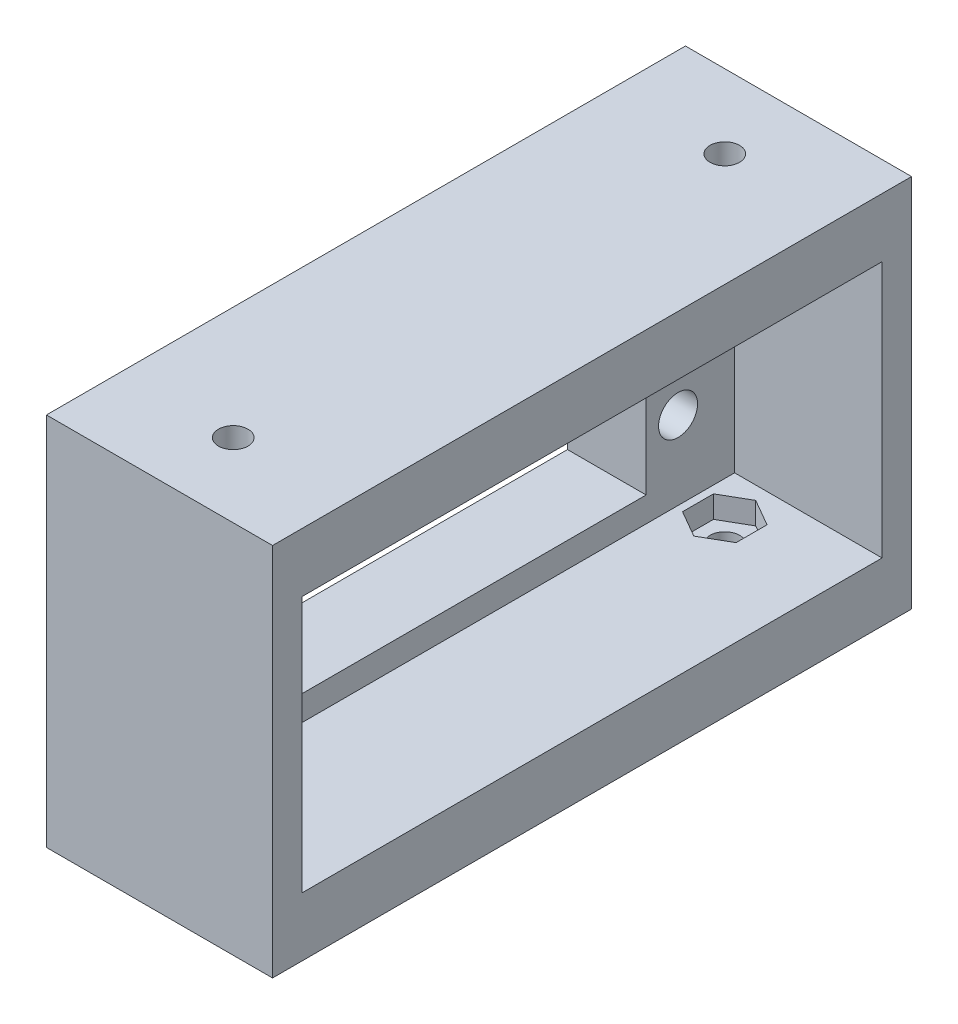
SolidWorks part; units mm, degrees
ref_plane "Front Plane" through (0, 0, 0) normal (0, 0, 1) x (1, 0, 0)
ref_plane "Top Plane" through (0, 0, 0) normal (0, 1, 0) x (1, 0, 0)
ref_plane "Right Plane" through (0, 0, 0) normal (1, 0, 0) x (0, 0, -1)
sketch "Sketch1" plane through (0, 0, 0) normal (1, 0, 0) x (0, 0, -1)
  line L0 (-20.5, 10.5) -> (20.5, 10.5)
  line L1 (-20.5, 10.5) -> (-20.5, -10.5)
  line L2 (-20.5, -10.5) -> (20.5, -10.5)
  line L3 (20.5, 10.5) -> (20.5, -10.5)
  line L5 (-32.5, 19.05) -> (32.5, 19.05)
  line L6 (-32.5, 19.05) -> (-32.5, -19.05)
  line L7 (-32.5, -19.05) -> (32.5, -19.05)
  line L8 (32.5, 19.05) -> (32.5, -19.05)
  point P4 (0, 10.5)
  point P6 (20.5, 0)
  point P11 (0, 19.05)
  point P12 (32.5, 0)
  dimension "D1" = 41
  dimension "D2" = 21
  dimension "D3" = 12
  dimension "D4" = 19.05
extrude "Boss-Extrude1" add sketch "Sketch1" along normal blind 8
sketch "Sketch2" plane through (8, 0, 0) normal (1, 0, 0) x (0, 0, -1)
  line L1 (-32.5, 19.05) -> (32.5, 19.05)
  line L2 (-32.5, 19.05) -> (-32.5, -19.05)
  line L3 (-32.5, -19.05) -> (32.5, -19.05)
  line L4 (32.5, 19.05) -> (32.5, -19.05)
  line L5 (-29.5, 13.05) -> (29.5, 13.05)
  line L6 (-29.5, 13.05) -> (-29.5, -13.05)
  line L7 (-29.5, -13.05) -> (29.5, -13.05)
  line L8 (29.5, 13.05) -> (29.5, -13.05)
  point P10 (0, -13.05)
  point P12 (-29.5, 0)
  dimension "D1" = 6
  dimension "D2" = 3
extrude "Boss-Extrude2" add sketch "Sketch2" along normal blind 15
hole_wizard "5/32 (0.15625) Diameter Hole1" positions "Sketch3" profile "Sketch4" hole size "5/32" standard "ANSI Inch" end condition through all
sketch "Sketch3" plane through (0, 0, 0) normal (-1, 0, 0) x (0, 0, 1)
  line L0 (23.749, 5.08) -> (23.749, -5.08) construction
  line L1 (23.749, -5.08) -> (-23.749, -5.08) construction
  line L2 (-23.749, -5.08) -> (-23.749, 5.08) construction
  line L3 (-23.749, 5.08) -> (23.749, 5.08) construction
  point P0 (-23.6085, 5.1229)
  point P2 (-23.749, -5.08)
  point P4 (23.749, -5.08)
  point P7 (23.749, 5.08)
sketch "Sketch4" plane through (0, 5.1229, -23.6085) normal (0, 1, 0) x (0, 0, 1)
  line L0 (0, 0) -> (0, 23)
  line L1 (0, 23) -> (1.9844, 23)
  line L2 (1.9844, 23) -> (1.9844, 0)
  line L5 (1.9844, 0) -> (0, 0)
  line L11 (0, -6.35) -> (0, 107.95) construction
  dimension "Thru Hole Dia." = 3.9688
  dimension "Thru Hole Depth" = 23
hole_wizard "Ø3.0mm Dowel Hole1" positions "Sketch5" profile "Sketch6" hole size "Ø3.0" standard "ANSI Metric"
sketch "Sketch5" plane through (0, -13.05, 0) normal (0, 1, 0) x (1, 0, 0)
  line L0 (11.5, 25) -> (11.5, -25) construction
  line L2 (0, 0) -> (23, 0) construction
  line L3 (0, 32.5) -> (0, -32.5) construction
  line L4 (23, 32.5) -> (23, -32.5) construction
  point P0 (11.5, 25)
  point P2 (11.5, -25)
  point P15 (11.5, 0)
  point P17 (11.5, 0)
  dimension "D1" = 50
sketch "Sketch6" plane through (11.5, -13.05, -25) normal (1, 0, 0) x (0, 0, 1)
  line L0 (0, 0) -> (0, 6)
  line L1 (0, 6) -> (1.5, 6)
  line L2 (1.5, 6) -> (1.5, 0)
  line L5 (1.5, 0) -> (0, 0)
  line L11 (0, -6.35) -> (0, 107.95) construction
  dimension "Thru Hole Dia." = 3
  dimension "Thru Hole Depth" = 6
mirror "Mirror1" about plane through (0, 0, 0) normal (0, 1, 0) of "Ø3.0mm Dowel Hole1"
sketch "Sketch7" plane through (0, -13.05, 0) normal (0, 1, 0) x (1, 0, 0)
  line L0 (0, 32.5) -> (0, -32.5) construction
  line L1 (8.775, -26.5733) -> (11.5, -28.1466)
  line L2 (11.5, -28.1466) -> (14.225, -26.5733)
  line L3 (14.225, -26.5733) -> (14.225, -23.4267)
  line L4 (14.225, -23.4267) -> (11.5, -21.8534)
  line L5 (11.5, -21.8534) -> (8.775, -23.4267)
  line L6 (8.775, -23.4267) -> (8.775, -26.5733)
  circle A0 centre (11.5, -25) radius 2.725 construction
  dimension "D1" = 5.45
extrude "Cut-Extrude1" cut sketch "Sketch7" against normal blind 2.25
mirror "Mirror2" about plane through (0, 0, 0) normal (0, 1, 0) of "Cut-Extrude1" second plane through (0, 0, 0) second plane normal (0, 0, 1)
